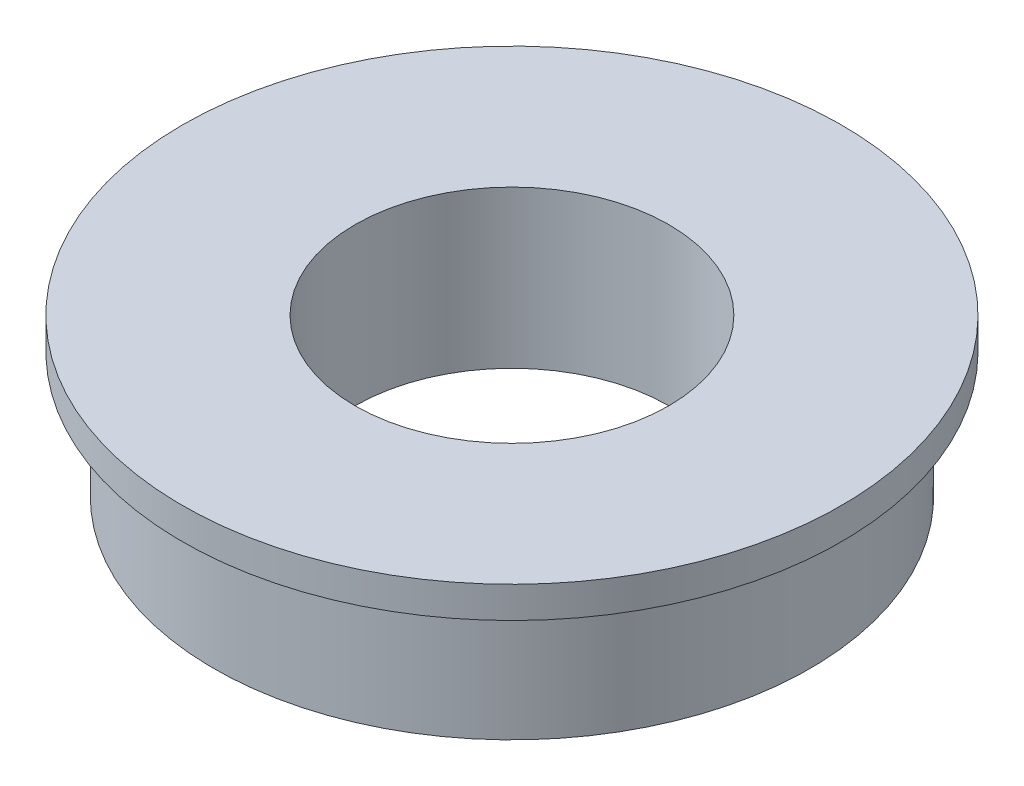
SolidWorks part; units mm, degrees
ref_plane "前视基准面" through (0, 0, 0) normal (0, 0, 1) x (1, 0, 0)
ref_plane "上视基准面" through (0, 0, 0) normal (0, 1, 0) x (1, 0, 0)
ref_plane "右视基准面" through (0, 0, 0) normal (1, 0, 0) x (0, 0, -1)
sketch "草图1" plane through (0, 0, 0) normal (0, 0, 1) x (1, 0, 0)
  line L0 (0, 8.4539) -> (0, -2.5329) construction
  line L1 (5, 2.4671) -> (10.5, 2.4671)
  line L2 (10.5, 2.4671) -> (10.5, 1.4671)
  line L3 (10.5, 1.4671) -> (9.5, 1.4671)
  line L4 (9.5, 1.4671) -> (9.5, -2.5329)
  line L5 (9.5, -2.5329) -> (5, -2.5329)
  line L6 (5, -2.5329) -> (5, 2.4671)
  dimension "D1" = 5
  dimension "D2" = 9.5
  dimension "D3" = 10.5
revolve "旋转1" add sketch "草图1" angle 360 about L0
